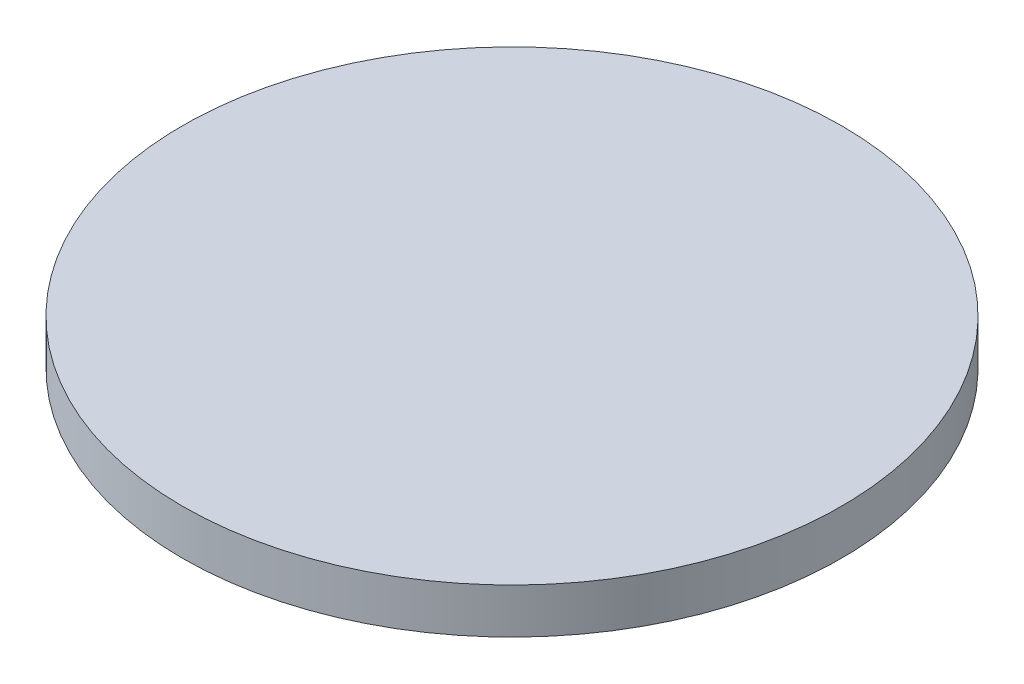
SolidWorks part; units mm, degrees
material "A-Glass Fiber"
ref_plane "Front Plane" through (0, 0, 0) normal (0, 0, 1) x (1, 0, 0)
ref_plane "Top Plane" through (0, 0, 0) normal (0, 1, 0) x (1, 0, 0)
ref_plane "Right Plane" through (0, 0, 0) normal (1, 0, 0) x (0, 0, -1)
sketch "Sketch1" plane through (0, 0, 0) normal (0, 1, 0) x (1, 0, 0)
  circle A0 centre (0, 0) radius 17.399
  dimension "D1" = 34.798
extrude "Boss-Extrude1" add sketch "Sketch1" along normal blind 2.3813
